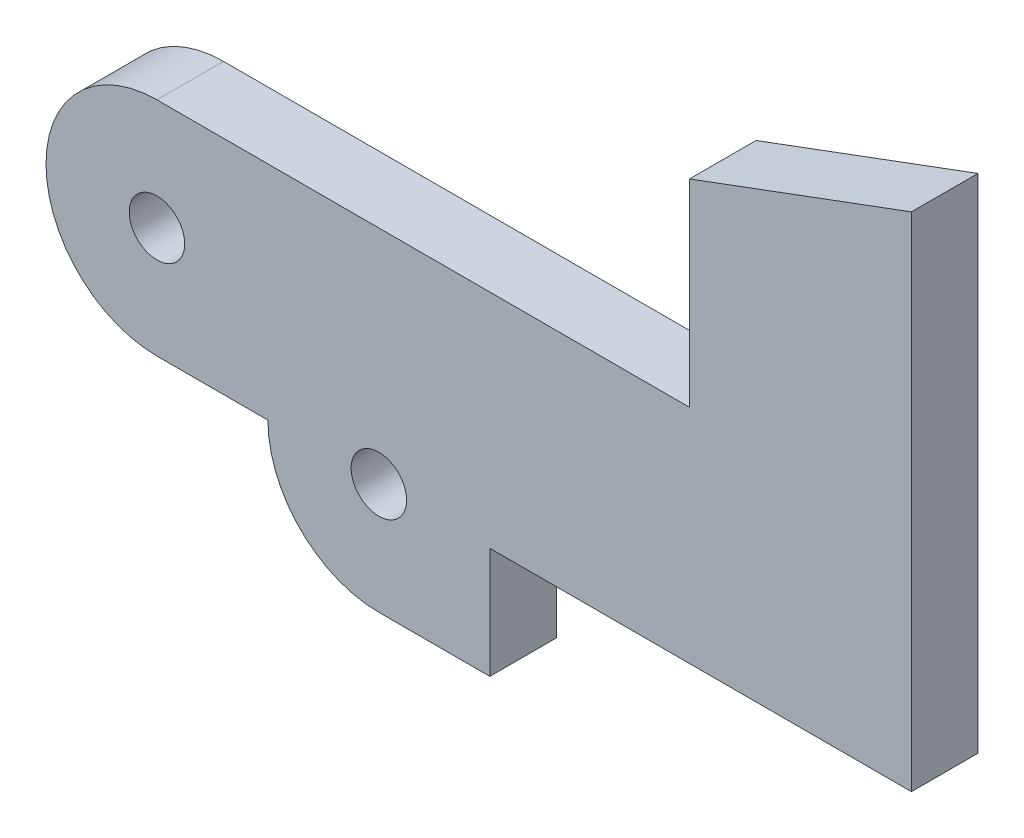
SolidWorks part; units mm, degrees
ref_plane "Front Plane" through (0, 0, 0) normal (0, 0, 1) x (1, 0, 0)
ref_plane "Top Plane" through (0, 0, 0) normal (0, 1, 0) x (1, 0, 0)
ref_plane "Right Plane" through (0, 0, 0) normal (1, 0, 0) x (0, 0, -1)
sketch "Sketch2" plane through (0, 0, 0) normal (0, 0, 1) x (1, 0, 0)
  line L0 (-69.6861, 39.7463) -> (-34.6861, 39.7463)
  line L1 (-34.6861, 39.7463) -> (-34.6861, 59.7463)
  line L2 (-34.6861, 59.7463) -> (-69.6861, 49.7463)
  arc A0 (-69.6861, 49.7463) -> (-69.6861, 39.7463) centre (-69.6861, 44.7463) ccw
  circle A1 centre (-69.6861, 44.7463) radius 1.5
extrude "Boss-Extrude3" add sketch "Sketch2" along normal blind 3
sketch "Sketch3" plane through (0, 0, 3) normal (0, 0, 1) x (1, 0, 0)
  line L0 (-64.6861, 39.7463) -> (-59.6861, 39.7463)
  line L1 (-69.6861, 39.7463) -> (-34.6861, 39.7463) construction
  line L2 (-59.6861, 39.7463) -> (-54.6861, 39.7463)
  arc A0 (-64.6861, 39.7463) -> (-54.6861, 39.7463) centre (-59.6861, 39.7463) ccw
extrude "Boss-Extrude4" add sketch "Sketch3" against normal blind 3
sketch "Sketch4" plane through (0, 0, 3) normal (0, 0, 1) x (1, 0, 0)
  circle A0 centre (-59.6861, 39.7463) radius 1.25
extrude "Cut-Extrude1" cut sketch "Sketch4" against normal blind 3
sketch "Sketch5" plane through (0, 0, 3) normal (0, 0, 1) x (1, 0, 0)
  line L0 (-34.6861, 59.7463) -> (-34.6861, 62.7463)
  line L1 (-34.6861, 62.7463) -> (-69.6861, 49.7463)
  line L2 (-69.6861, 49.7463) -> (-34.6861, 59.7463)
extrude "Boss-Extrude5" add sketch "Sketch5" against normal blind 3
sketch "Sketch6" plane through (0, 0, 3) normal (0, 0, 1) x (1, 0, 0)
  line L0 (-34.6861, 39.7463) -> (-35.6861, 39.7463)
  line L1 (-54.6861, 39.7463) -> (-34.6861, 39.7463) construction
  line L2 (-35.6861, 39.7463) -> (-35.6861, 63.56)
  line L3 (-35.6861, 63.56) -> (-33.928, 63.56)
  line L4 (-33.928, 63.56) -> (-33.928, 39.7463)
  line L5 (-33.928, 39.7463) -> (-34.6861, 39.7463)
extrude "Cut-Extrude2" cut sketch "Sketch6" against normal blind 3
sketch "Sketch7" plane through (0, 0, 3) normal (0, 0, 1) x (1, 0, 0)
  circle A0 centre (-69.6861, 44.7463) radius 1.5
  circle A1 centre (-69.6861, 44.7463) radius 1.25
extrude "Boss-Extrude6" add sketch "Sketch7" against normal blind 3
sketch "Sketch8" plane through (0, 0, 3) normal (0, 0, 1) x (1, 0, 0)
  line L0 (-69.6861, 49.7463) -> (-45.6861, 49.7463)
  line L1 (-45.6861, 49.7463) -> (-45.6861, 58.6606)
  line L2 (-35.6861, 62.3749) -> (-69.6861, 49.7463) construction
  line L3 (-45.6861, 58.6606) -> (-69.6861, 49.7463)
extrude "Cut-Extrude3" cut sketch "Sketch8" against normal blind 10
sketch "Sketch9" plane through (0, 0, 3) normal (0, 0, 1) x (1, 0, 0)
  line L0 (-59.6861, 34.7463) -> (-54.6861, 34.7463)
  line L1 (-54.6861, 34.7463) -> (-54.6861, 39.7463)
  arc A0 (-64.6861, 39.7463) -> (-54.6861, 39.7463) centre (-59.6861, 39.7463) ccw construction
  arc A1 (-59.6861, 34.7463) -> (-54.6861, 39.7463) centre (-59.6861, 39.7463) ccw
extrude "Boss-Extrude7" add sketch "Sketch9" against normal blind 3
